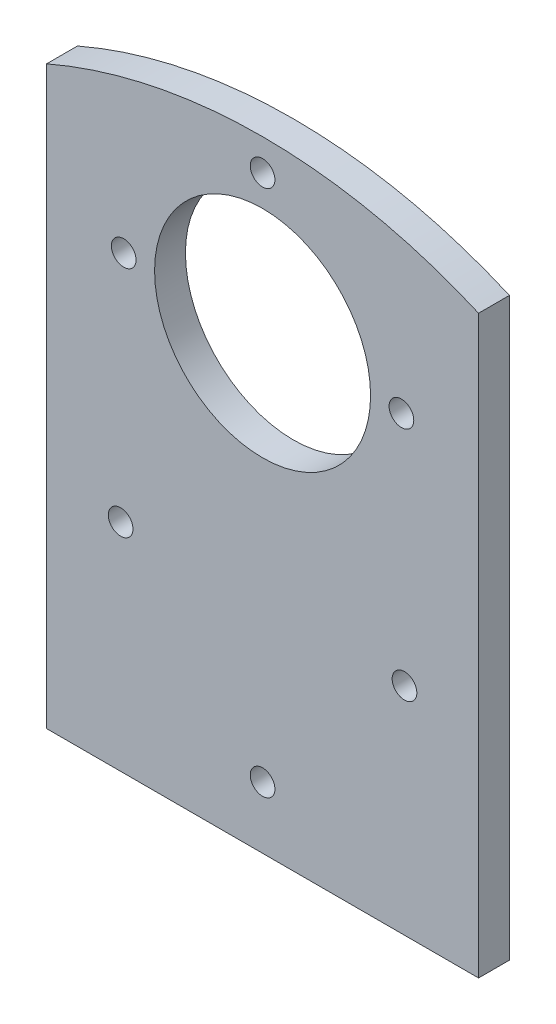
SolidWorks part; units mm, degrees
material "6061 Alloy"
ref_plane "Front Plane" through (0, 0, 0) normal (0, 0, 1) x (1, 0, 0)
ref_plane "Top Plane" through (0, 0, 0) normal (0, 1, 0) x (1, 0, 0)
ref_plane "Right Plane" through (0, 0, 0) normal (1, 0, 0) x (0, 0, -1)
sketch "Sketch1" plane through (0, 0, 0) normal (0, 0, 1) x (1, 0, 0)
  line L1 (35, -52.5) -> (-35, -52.5)
  line L2 (35, -52.5) -> (35, 52.5)
  line L3 (35, 52.5) -> (-35, 52.5)
  line L4 (-35, -52.5) -> (-35, 52.5)
  line L5 (35, -52.5) -> (-35, 52.5) construction
  line L6 (35, 52.5) -> (-35, -52.5) construction
  point P0 (0, 0)
  dimension "D1" = 70
  dimension "D2" = 105
extrude "Boss-Extrude1" add sketch "Sketch1" along normal blind 5
sketch "Sketch2" plane through (0, 0, 0) normal (0, 0, -1) x (-1, 0, 0)
  line L0 (-35, -2.5) -> (35, -2.5) construction
  line L1 (-35, -52.5) -> (-35, 52.5) construction
  line L2 (35, 52.5) -> (35, -52.5) construction
  line L3 (35, -52.5) -> (-35, -52.5) construction
  circle A0 centre (0, 20.5) radius 17.5
  point P11 (0, -2.5)
  dimension "D2" = 35
  dimension "D1" = 50
  dimension "D3" = 23
  dimension "D4" = 35
extrude "Cut-Extrude3" cut sketch "Sketch2" against normal through all
sketch "Sketch3" plane through (0, 0, 5) normal (0, 0, 1) x (1, 0, 0)
  circle A5 centre (0, 20.5) radius 17.5 construction
  circle A6 centre (-22.5, 20.5) radius 2
  circle A7 centre (0, 43) radius 2
  circle A8 centre (22.5, 20.5) radius 2
  point P0 (0, 20.5)
  dimension "D2" = 22.5
  dimension "D3" = 22.5
  dimension "D4" = 4
  dimension "D5" = 4
  dimension "D6" = 4
  dimension "D1" = 22.5
extrude "Cut-Extrude4" cut sketch "Sketch3" against normal through all
sketch "Sketch4" plane through (0, 0, 5) normal (0, 0, 1) x (1, 0, 0)
  line L0 (0, 0) -> (0, -52.5) construction
  line L1 (-35, -52.5) -> (35, -52.5) construction
  circle A0 centre (0, -42.5) radius 2
  circle A1 centre (-23, -17.5) radius 2
  circle A3 centre (23, -17.5) radius 2
  dimension "D3" = 4
  dimension "D1" = 10
  dimension "D2" = 25
  dimension "D4" = 23
extrude "Cut-Extrude5" cut sketch "Sketch4" against normal blind 5
sketch "Sketch5" plane through (0, 0, 5) normal (0, 0, 1) x (1, 0, 0)
  line L0 (-35, 40.7935) -> (35, 40.7935) construction
  line L1 (-35, 52.5) -> (-35, -52.5) construction
  line L2 (35, -52.5) -> (35, 52.5) construction
  line L3 (-35, 40.7935) -> (-35, 52.5)
  line L4 (-35, 52.5) -> (35, 52.5)
  line L5 (35, 52.5) -> (35, 40.7935)
  arc A0 (-35, 40.7935) -> (35, 40.7935) centre (0, -39.6661) cw
extrude "Cut-Extrude6" cut sketch "Sketch5" against normal blind 10
